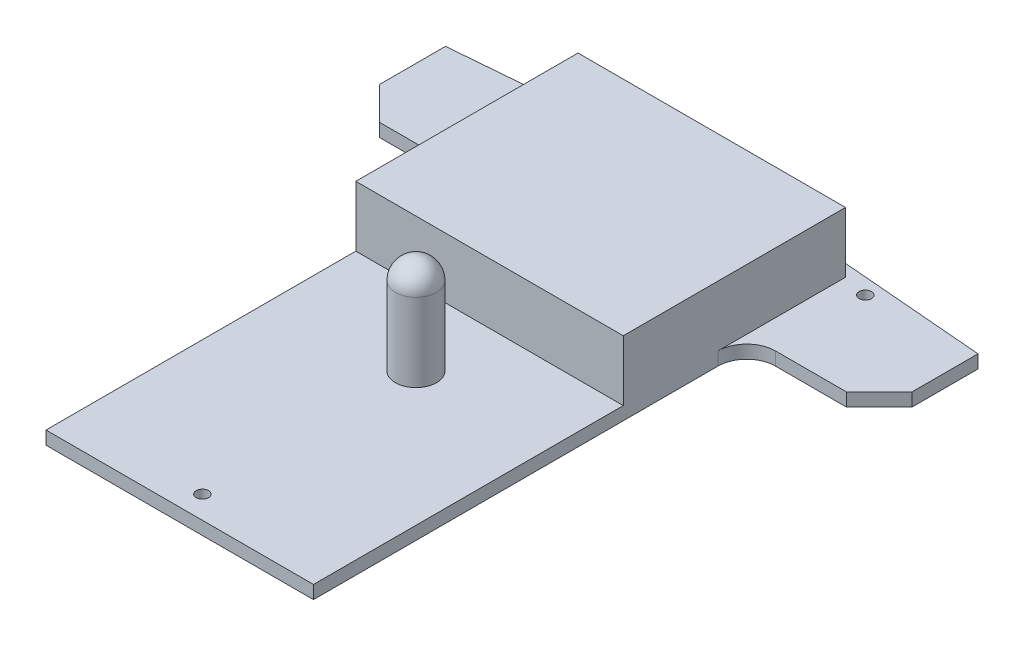
SolidWorks part; units mm, degrees
ref_plane "Front Plane" through (0, 0, 0) normal (0, 0, 1) x (1, 0, 0)
ref_plane "Top Plane" through (0, 0, 0) normal (0, 1, 0) x (1, 0, 0)
ref_plane "Right Plane" through (0, 0, 0) normal (1, 0, 0) x (0, 0, -1)
sketch "Sketch1" plane through (0, 0, 0) normal (0, 1, 0) x (1, 0, 0)
  line L0 (-16.25, 0) -> (16.25, 0)
  line L1 (16.25, 0) -> (16.25, 49.14)
  line L2 (-16.25, 0) -> (-16.25, 49.14)
  line L3 (-19.75, 52.64) -> (-28.35, 52.64)
  line L4 (19.75, 52.64) -> (28.35, 52.64)
  line L5 (28.35, 52.64) -> (32.35, 56.64)
  line L6 (32.35, 56.64) -> (32.35, 64.64)
  line L7 (-28.35, 52.64) -> (-32.35, 56.64)
  line L8 (-32.35, 56.64) -> (-32.35, 64.64)
  line L9 (32.35, 64.64) -> (8.35, 66.64)
  line L10 (8.35, 66.64) -> (8.35, 64.64)
  line L11 (8.35, 64.64) -> (-8.35, 64.64)
  line L12 (-8.35, 64.64) -> (-8.35, 66.64)
  line L13 (-8.35, 66.64) -> (-32.35, 64.64)
  line L14 (-18.58, 63.9689) -> (18.58, 63.9689) construction
  line L15 (19.33, 63.9689) -> (19.3923, 64.7163) construction
  line L16 (19.3923, 64.7163) -> (19.4753, 65.7129) construction
  line L18 (0, 2) -> (0, 0) construction
  arc A0 (16.25, 49.14) -> (19.75, 52.64) centre (19.75, 49.14) cw
  arc A1 (-16.25, 49.14) -> (-19.75, 52.64) centre (-19.75, 49.14) ccw
  circle A2 centre (-19.33, 63.9689) radius 0.75
  circle A3 centre (19.33, 63.9689) radius 0.75
  circle A4 centre (0, 2.75) radius 0.75
  point P4 (0, 0)
  point P11 (16.25, 52.64)
  point P24 (0, 64.64)
  point P32 (0, 63.9689)
  dimension "D3" = 3.5
  dimension "D12" = 1.5
  dimension "D1" = 32.5
  dimension "D2" = 52.64
  dimension "D4" = 12.1
  dimension "D5" = 45
  dimension "D6" = 4
  dimension "D7" = 12
  dimension "D8" = 24
  dimension "D9" = 2
  dimension "D10" = 2
  dimension "D11" = 37.16
  dimension "D13" = 1
  dimension "D14" = 2
extrude "Boss-Extrude1" add sketch "Sketch1" along normal blind 1.6
sketch "Sketch2" plane through (0, 1.6, 0) normal (0, 1, 0) x (1, 0, 0)
  line L0 (16.25, 0) -> (16.25, 49.14) construction
  line L1 (-16.25, 37.64) -> (16.25, 37.64)
  line L2 (-16.25, 37.64) -> (-16.25, 64.64)
  line L3 (-16.25, 64.64) -> (16.25, 64.64)
  line L4 (16.25, 37.64) -> (16.25, 64.64)
  line L5 (-16.25, 49.14) -> (-16.25, 0) construction
  dimension "D1" = 27
extrude "Boss-Extrude2" add sketch "Sketch2" along normal blind 7.35 contours L1 L4 L3 L2
sketch "Sketch3" plane through (0, 1.6, 0) normal (0, 1, 0) x (1, 0, 0)
  line L0 (-16.25, 0) -> (16.25, 0) construction
  circle A0 centre (0, 28.7) radius 2.5
  point P4 (0, 0)
  dimension "D2" = 5
  dimension "D1" = 28.7
extrude "Boss-Extrude3" add sketch "Sketch3" along normal blind 12
fillet "Fillet1" radius 2.5 1 edges at (0, 13.6, -26.2)
